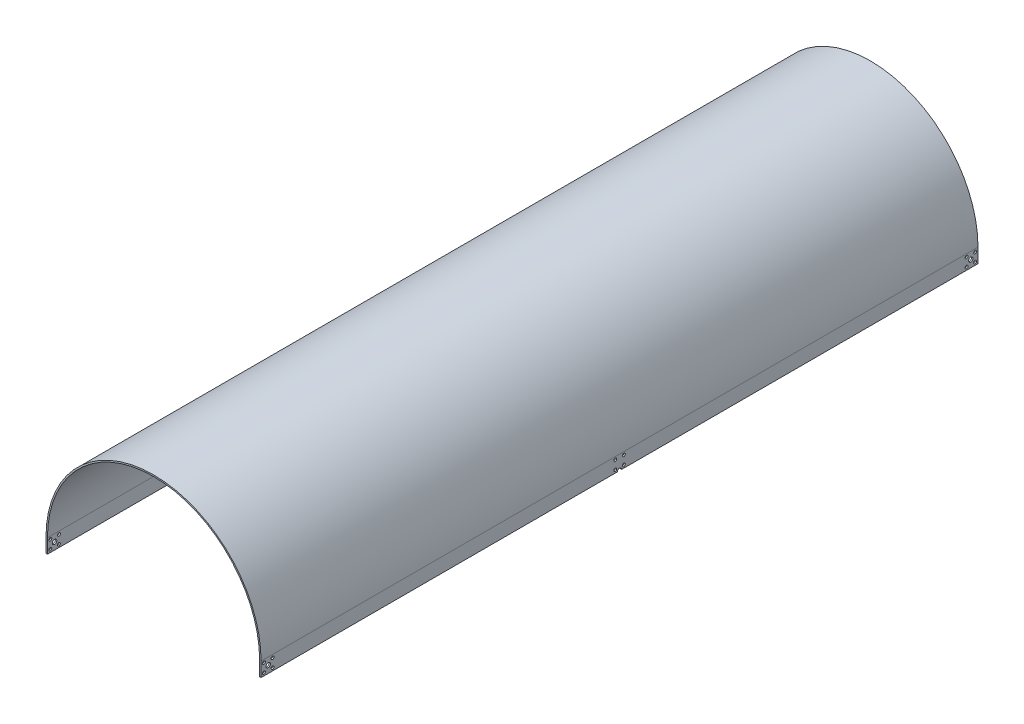
SolidWorks part; units mm, degrees
ref_plane "Plan de face" through (0, 0, 0) normal (0, 0, 1) x (1, 0, 0)
ref_plane "Plan de dessus" through (0, 0, 0) normal (0, 1, 0) x (1, 0, 0)
ref_plane "Plan de droite" through (0, 0, 0) normal (1, 0, 0) x (0, 0, -1)
sketch "Esquisse1" plane through (0, 0, 0) normal (0, 0, 1) x (1, 0, 0)
  line L0 (-215.489, 0) -> (178.991, 0) construction
  line L1 (0, 150) -> (0, 148)
  line L2 (-150, -20) -> (-148, -20)
  line L3 (-150, 0) -> (-150, -20)
  line L5 (-148, 0) -> (-148, -20)
  line L6 (0, 166.6964) -> (0, -195.0929) construction
  line L8 (-148, 166.6964) -> (-148, -195.0929) construction
  line L9 (-150, 166.6964) -> (-150, -195.0929) construction
  line L10 (-215.489, -20) -> (178.991, -20) construction
  arc A1 (0, 148) -> (-148, 0) centre (0, 0) ccw
  arc A6 (0, 150) -> (-150, 0) centre (0, 0) ccw
  point P13 (150, 166.6964)
  point P14 (150, -195.0929)
  point P17 (148, 166.6964)
  point P18 (148, -195.0929)
  point P19 (148, 0)
  point P22 (143.4457, 43.8558)
  dimension "D3" = 20
extrude "Boss.-Extru.1" add sketch "Esquisse1" along normal blind 1000
sketch "Esquisse2" plane through (-150, 0, 0) normal (-1, 0, 0) x (0, 0, 1)
  line L0 (1000, -20) -> (0, -20) construction
  circle A0 centre (10, -10) radius 3.05
  circle A2 centre (990, -10) radius 3.05
  circle A3 centre (500, -10) radius 3.05 [skipped]
  dimension "D1" = 10
  dimension "D2" = 3
extrude "Enlèv. mat.-Extru.1" cut sketch "Esquisse2" against normal blind 500
sketch "Esquisse3" plane through (-150, 0, 0) normal (-1, 0, 0) x (0, 0, 1)
  line L0 (10, -24.3966) -> (10, 4.854) construction
  line L1 (1000, -20) -> (0, -20) construction
  circle A0 centre (4, -4) radius 2.05
  circle A1 centre (16, -4) radius 2.05
  circle A2 centre (4, -16) radius 2.05
  circle A3 centre (16, -16) radius 2.05
  circle A4 centre (494, -4) radius 2.05
  circle A5 centre (506, -4) radius 2.05
  circle A6 centre (494, -16) radius 2.05
  circle A7 centre (506, -16) radius 2.05
  circle A8 centre (984, -4) radius 2.05
  circle A9 centre (996, -4) radius 2.05
  circle A10 centre (984, -16) radius 2.05
  circle A11 centre (996, -16) radius 2.05
  dimension "D1" = 12
  dimension "D2" = 12
  dimension "D3" = 6
  dimension "D4" = 6
  dimension "D5" = 4
  dimension "D6" = 12
  dimension "D7" = 3
extrude "Enlèv. mat.-Extru.2" cut sketch "Esquisse3" against normal blind 5
mirror "Symétrie2" about plane through (0, 150, 1000) normal (-1, 0, 0) of bodies 104
sketch "Esquisse4" plane through (-150, 0, 0) normal (-1, 0, 0) x (0, 0, 1)
  line L0 (1000, -20) -> (0, -20) construction
  circle A0 centre (500, -20) radius 3.1
extrude "Enlèv. mat.-Extru.3" cut sketch "Esquisse4" against normal blind 310
